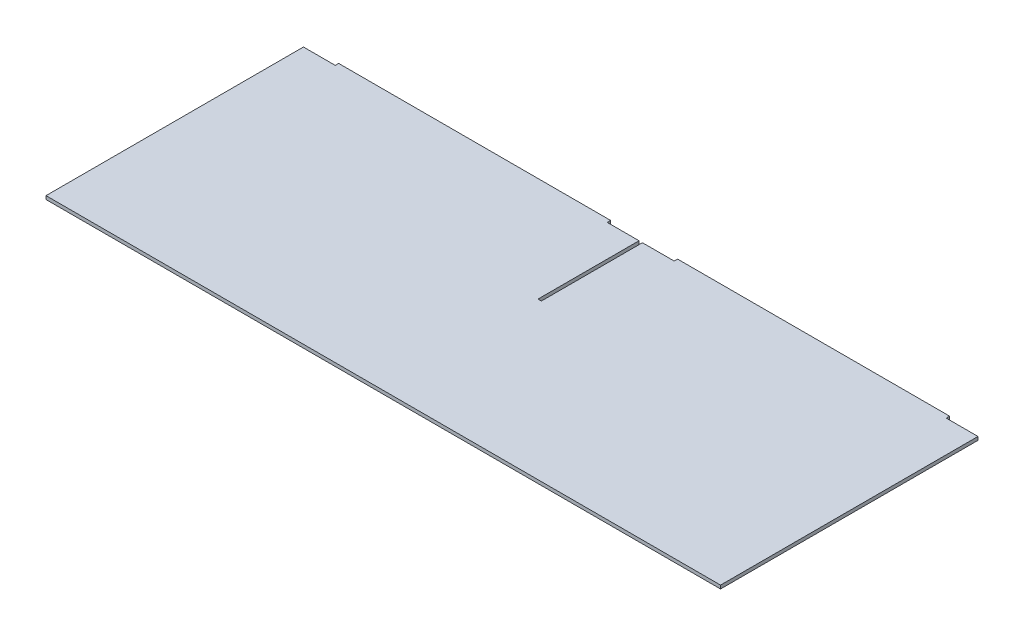
SolidWorks part; units mm, degrees
material "6061-T6 (SS)"
ref_plane "X-Y Datum" through (0, 0, 0) normal (0, 0, 1) x (1, 0, 0)
ref_plane "X-Z Datum" through (0, 0, 0) normal (0, 1, 0) x (1, 0, 0)
ref_plane "Y-Z Datum" through (0, 0, 0) normal (1, 0, 0) x (0, 0, -1)
sketch "Sketch1" plane through (0, 0, 0) normal (0, 1, 0) x (1, 0, 0)
  line L1 (0, 0) -> (629.9098, 0)
  line L2 (0, 0) -> (0, 147.6985)
  line L3 (0, 147.6985) -> (629.9098, 147.6985)
  line L4 (629.9098, 0) -> (629.9098, 147.6985)
extrude "Boss-Extrude1" add sketch "Sketch1" along normal blind 3.175
sketch "Sketch3" plane through (0, 0, -147.6985) normal (0, 0, -1) x (-1, 0, 0)
  line L0 (-629.9098, 0) -> (0, 0) construction
  line L1 (-629.9098, 0) -> (-629.9098, 3.175) construction
  line L2 (-629.9098, 3.175) -> (0, 3.175) construction
  line L3 (0, 0) -> (0, 3.175) construction
  line L4 (-600.2261, 0) -> (-346.2261, 0)
  line L5 (-600.2261, 0) -> (-600.2261, 3.175)
  line L6 (-600.2261, 3.175) -> (-346.2261, 3.175)
  line L7 (-346.2261, 0) -> (-346.2261, 3.175)
  line L8 (-283.6837, 0) -> (-29.6837, 0)
  line L9 (-283.6837, 0) -> (-283.6837, 3.175)
  line L10 (-283.6837, 3.175) -> (-29.6837, 3.175)
  line L11 (-29.6837, 0) -> (-29.6837, 3.175)
extrude "Boss-Extrude2" add sketch "Sketch3" along normal blind 3.175
sketch "Sketch4" plane through (0, 3.175, 0) normal (0, 1, 0) x (1, 0, 0)
  line L0 (346.2261, 147.6985) -> (283.6837, 147.6985) construction
  line L1 (313.3674, 53.332) -> (316.5424, 53.332)
  line L2 (313.3674, 53.332) -> (313.3674, 242.0649)
  line L3 (313.3674, 242.0649) -> (316.5424, 242.0649)
  line L4 (316.5424, 53.332) -> (316.5424, 242.0649)
  line L5 (313.3674, 53.332) -> (316.5424, 242.0649) construction
  line L6 (313.3674, 242.0649) -> (316.5424, 53.332) construction
  point P0 (314.9549, 147.6985)
extrude "Cut-Extrude1" cut sketch "Sketch4" against normal blind 3.175
sketch "Sketch6" plane through (0, 3.175, 0) normal (0, 1, 0) x (1, 0, 0)
  line L0 (314.9549, 53.332) -> (314.9549, 202.815) construction
  line L6 (629.9098, 36.9246) -> (633.0848, 36.9246)
  line L7 (633.0848, 147.6985) -> (633.0848, 36.9246)
  line L8 (629.9098, 147.6985) -> (633.0848, 147.6985)
  line L9 (629.9098, 147.6985) -> (629.9098, 36.9246)
  line L10 (0, 147.6985) -> (0, 36.9246)
  line L11 (0, 147.6985) -> (-3.175, 147.6985)
  line L12 (-3.175, 147.6985) -> (-3.175, 36.9246)
  line L13 (0, 36.9246) -> (-3.175, 36.9246)
sketch "Sketch7" plane through (0, 3.175, 0) normal (0, 1, 0) x (1, 0, 0)
  line L1 (0, 0) -> (629.9098, 0)
  line L2 (0, 0) -> (0, -92.71)
  line L3 (0, -92.71) -> (629.9098, -92.71)
  line L4 (629.9098, 0) -> (629.9098, -92.71)
  dimension "D1" = 92.71
extrude "Boss-Extrude3" add sketch "Sketch7" against normal through all
